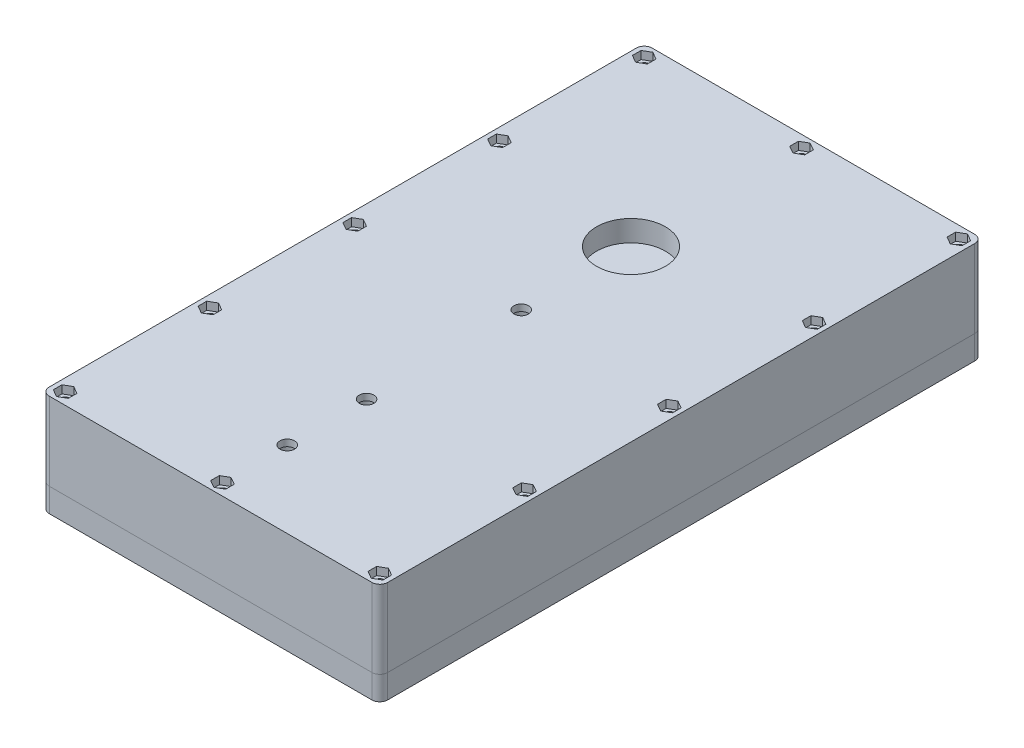
SolidWorks part; units mm, degrees
other "Gearbox lid"
other "Gearbox body"
ref_plane "Front Plane" through (0, 0, 0) normal (0, 0, 1) x (1, 0, 0)
ref_plane "Top Plane" through (0, 0, 0) normal (0, 1, 0) x (1, 0, 0)
ref_plane "Right Plane" through (0, 0, 0) normal (1, 0, 0) x (0, 0, -1)
sketch "Sketch1" plane through (0, 0, 0) normal (0, 1, 0) x (1, 0, 0)
  line L1 (75, -90) -> (-75, -90) construction
  line L2 (75, -90) -> (75, 90) construction
  line L3 (75, 90) -> (-75, 90) construction
  line L4 (-75, -90) -> (-75, 90) construction
  line L5 (0, 90) -> (0, -90) construction
  line L6 (75, 0) -> (-75, 0) construction
  line L7 (15.5, -75.5) -> (-15.5, -75.5) construction
  line L8 (15.5, -75.5) -> (15.5, -44.5) construction
  line L9 (15.5, -44.5) -> (-15.5, -44.5) construction
  line L10 (-15.5, -75.5) -> (-15.5, -44.5) construction
  line L11 (0, -44.5) -> (0, -75.5) construction
  line L12 (15.5, -60) -> (-15.5, -60) construction
  line L13 (-55, 130) -> (55, 130)
  line L14 (-55, 130) -> (-55, -80)
  line L15 (-55, -80) -> (55, -80)
  line L16 (55, 130) -> (55, -80)
  circle A0 centre (0, 70) radius 50 construction
  circle A1 centre (0, 0) radius 20 construction
  circle A3 centre (0, 0) radius 45 construction
  circle A4 centre (0, -60) radius 15 construction
  circle A5 centre (0, 0) radius 3.15
  circle A6 centre (0, -60) radius 2.75
  circle A7 centre (0, 70) radius 13
  point P0 (0, 0)
  dimension "D3" = 160
  dimension "D4" = 31
  dimension "D5" = 30
  dimension "D6" = 90
  dimension "D7" = 40
  dimension "D8" = 130
  dimension "D10" = 26
  dimension "D12" = 6.3
  dimension "D13" = 5.5
  dimension "D14" = 100
  dimension "D2" = 150
  dimension "D9" = 80
  dimension "D11" = 110
extrude "Boss-Extrude1" add sketch "Sketch1" along normal blind 8
sketch "Sketch2" plane through (0, 0, 0) normal (0, -1, 0) x (1, 0, 0)
  line L0 (-64, 89) -> (-64, -139)
  line L1 (-55, 80) -> (55, 80)
  line L2 (-55, 80) -> (-55, -130)
  line L3 (-55, -130) -> (55, -130)
  line L4 (55, 80) -> (55, -130)
  line L5 (-64, -139) -> (64, -139)
  line L6 (64, 89) -> (64, -139)
  line L7 (-64, 89) -> (64, 89)
  line L8 (-55, 80) -> (-64, 89) construction
  line L9 (0, 0) -> (0, 89) construction
  line L10 (-55, -25) -> (55, -25) construction
  line L11 (-64, -25) -> (-55, -25) construction
  line L12 (-59.5, 84.5) -> (-59.5, -25) construction
  line L13 (59.5, 84.5) -> (59.5, -25) construction
  line L14 (64, -25) -> (55, -25) construction
  line L15 (55, 80) -> (64, 89) construction
  line L16 (55, -130) -> (64, -139) construction
  line L17 (0, -50) -> (0, -139) construction
  line L18 (-55, -130) -> (-64, -139) construction
  line L19 (-64, -139) -> (64, -139)
  line L20 (-55, -130) -> (55, -130)
  circle A0 centre (-59.5, 84.5) radius 1.75
  circle A1 centre (-59.5, -25) radius 1.75
  circle A2 centre (-59.5, 29.75) radius 1.75
  circle A3 centre (0, 84.5) radius 1.75
  circle A4 centre (59.5, 29.75) radius 1.75
  circle A5 centre (59.5, -25) radius 1.75
  circle A6 centre (59.5, 84.5) radius 1.75
  circle A7 centre (59.5, -134.5) radius 1.75
  circle A8 centre (59.5, -79.75) radius 1.75
  circle A9 centre (0, -134.5) radius 1.75
  circle A10 centre (-59.5, -79.75) radius 1.75
  circle A11 centre (-59.5, -134.5) radius 1.75
  line M3 (-55, 80) -> (-55, -130)
  line M4 (-55, -130) -> (55, -130)
  line M5 (55, -130) -> (55, 80)
  line M6 (55, 80) -> (-55, 80)
  dimension "D2" = 3.5
  dimension "D1" = 9
extrude "Boss-Extrude2" add sketch "Sketch2" along normal blind 21.5 and the other way up to surface (8 mm away) contours L7 L0 L5 L6 A10 A6 A4 A3 A2 A1 A0 A5 A7 A8 A9 A11 M3 M6 M5 M4 other way up to face at (0, 8, 3.15)
sketch "Sketch3" plane through (0, -21.5, 0) normal (0, -1, 0) x (1, 0, 0)
  line L1 (-64, 89) -> (64, 89)
  line L2 (-64, 89) -> (-64, -139)
  line L3 (-64, -139) -> (64, -139)
  line L4 (64, 89) -> (64, -139)
  line L5 (-15.5, 75.5) -> (15.5, 75.5) construction
  line L6 (-15.5, 75.5) -> (-15.5, 44.5) construction
  line L7 (-15.5, 44.5) -> (15.5, 44.5) construction
  line L8 (15.5, 75.5) -> (15.5, 44.5) construction
  line L9 (0, 44.5) -> (0, 75.5) construction
  line L10 (-15.5, 60) -> (15.5, 60) construction
  circle A0 centre (0, 60) radius 11.5
  circle A1 centre (-15.5, 75.5) radius 1.75
  circle A2 centre (15.5, 75.5) radius 1.75
  circle A3 centre (15.5, 44.5) radius 1.75
  circle A4 centre (-15.5, 44.5) radius 1.75
  circle A5 centre (-59.5, -134.5) radius 1.75 construction
  circle A6 centre (0, -134.5) radius 1.75 construction
  circle A7 centre (59.5, -134.5) radius 1.75 construction
  circle A8 centre (59.5, -79.75) radius 1.75 construction
  circle A9 centre (-59.5, -79.75) radius 1.75 construction
  circle A10 centre (-59.5, -25) radius 1.75 construction
  circle A11 centre (-59.5, 29.75) radius 1.75 construction
  circle A12 centre (59.5, -25) radius 1.75 construction
  circle A13 centre (59.5, 29.75) radius 1.75 construction
  circle A14 centre (59.5, 84.5) radius 1.75 construction
  circle A15 centre (0, 84.5) radius 1.75 construction
  circle A16 centre (-59.5, 84.5) radius 1.75 construction
  circle A17 centre (-59.5, -134.5) radius 1.75
  circle A18 centre (0, -134.5) radius 1.75
  circle A19 centre (59.5, -134.5) radius 1.75
  circle A20 centre (59.5, -79.75) radius 1.75
  circle A21 centre (-59.5, -79.75) radius 1.75
  circle A22 centre (-59.5, -25) radius 1.75
  circle A23 centre (-59.5, 29.75) radius 1.75
  circle A24 centre (59.5, -25) radius 1.75
  circle A25 centre (59.5, 29.75) radius 1.75
  circle A26 centre (59.5, 84.5) radius 1.75
  circle A27 centre (0, 84.5) radius 1.75
  circle A28 centre (-59.5, 84.5) radius 1.75
  circle A29 centre (0, 0) radius 3.15 construction
  circle A30 centre (0, 0) radius 3.15
  circle A31 centre (0, -70) radius 5.25
  point P4 (0, 60)
  dimension "D2" = 23
  dimension "D3" = 3.5
  dimension "D4" = 10.5
  dimension "D1" = 31
extrude "Boss-Extrude3" add sketch "Sketch3" along normal blind 9 separate body
sketch "Sketch4" plane through (0, -21.5, 0) normal (0, 1, 0) x (1, 0, 0)
  circle A0 centre (-15.5, -44.5) radius 2.86
  circle A1 centre (15.5, -44.5) radius 2.86
  circle A2 centre (15.5, -75.5) radius 2.86
  circle A3 centre (-15.5, -75.5) radius 2.86
  dimension "D1" = 5.72
extrude "Cut-Extrude1" cut sketch "Sketch4" against normal blind 3.5
sketch "Sketch5" plane through (0, 0, 0) normal (0, -1, 0) x (1, 0, 0)
  line L0 (0, 0) -> (0, -57) construction
  line L1 (0, 60) -> (0, 0) construction
  circle A0 centre (0, -28.5) radius 2.75
  circle A1 centre (0, 30) radius 2.75
  circle A2 centre (0, -70) radius 13 construction
  dimension "D1" = 5.5
extrude "Cut-Extrude2" cut sketch "Sketch5" against normal through all
sketch "Sketch6" plane through (0, 0, 0) normal (0, -1, 0) x (1, 0, 0)
  circle A0 centre (0, 30) radius 4.36
  circle A1 centre (0, -28.5) radius 4.36
  circle A2 centre (0, 60) radius 4.36
  dimension "D1" = 8.72
extrude "Cut-Extrude3" cut sketch "Sketch6" against normal blind 5.5
sketch "Sketch7" plane through (0, 8, 0) normal (0, 1, 0) x (1, 0, 0)
  circle A0 centre (0, 28.5) radius 7.5
  circle A1 centre (0, -30) radius 7.5
  circle A2 centre (0, -30) radius 2.75 construction
  circle A3 centre (0, 28.5) radius 2.75 construction
  circle A4 centre (0, -30) radius 2.75
  circle A5 centre (0, 28.5) radius 2.75
  dimension "D1" = 15
extrude "Boss-Extrude4" add sketch "Sketch7" along normal blind 22.5 separate body
fillet "Fillet1" radius 3 8 edges at (-55, -10.75, 80) (55, -10.75, 80) (55, -10.75, -130) (-55, -10.75, -130) (-64, -6.75, -139) (64, -6.75, -139) (64, -6.75, 89) (-64, -6.75, 89)
fillet "Fillet2" radius 3 4 edges at (-64, -26, 89) (64, -26, 89) (-64, -26, -139) (64, -26, -139)
sketch "Sketch8" plane through (0, -30.5, 0) normal (0, -1, 0) x (1, 0, 0)
  circle A0 centre (0, 0) radius 3.15 construction
  circle A1 centre (0, 0) radius 3.15
extrude "Boss-Extrude5" add sketch "Sketch8" against normal blind 3
sketch "Sketch9" plane through (0, 8, 0) normal (0, 1, 0) x (1, 0, 0)
  circle A0 centre (0, 0) radius 3.15 construction
  circle A1 centre (0, 0) radius 3.15
extrude "Boss-Extrude6" add sketch "Sketch9" against normal blind 3
sketch "Sketch10" plane through (0, 8, 0) normal (0, 1, 0) x (1, 0, 0)
  line L0 (-59.5, 134.5) -> (-59.5, 137.762) construction
  line L1 (-59.5, 137.762) -> (-62.325, 136.131)
  line L2 (-62.325, 136.131) -> (-62.325, 132.869)
  line L3 (-62.325, 132.869) -> (-59.5, 131.238)
  line L4 (-59.5, 131.238) -> (-56.675, 132.869)
  line L5 (-56.675, 132.869) -> (-56.675, 136.131)
  line L6 (-56.675, 136.131) -> (-59.5, 137.762)
  line L7 (0, 137.762) -> (-2.825, 136.131)
  line L8 (-2.825, 136.131) -> (-2.825, 132.869)
  line L9 (-2.825, 132.869) -> (0, 131.238)
  line L10 (0, 131.238) -> (2.825, 132.869)
  line L11 (2.825, 132.869) -> (2.825, 136.131)
  line L12 (2.825, 136.131) -> (0, 137.762)
  line L13 (-59.5, 83.012) -> (-62.325, 81.381)
  line L14 (-62.325, 81.381) -> (-62.325, 78.119)
  line L15 (-62.325, 78.119) -> (-59.5, 76.488)
  line L16 (-59.5, 76.488) -> (-56.675, 78.119)
  line L17 (-56.675, 78.119) -> (-56.675, 81.381)
  line L18 (-56.675, 81.381) -> (-59.5, 83.012)
  line L19 (-59.5, 28.262) -> (-62.325, 26.631)
  line L20 (-62.325, 26.631) -> (-62.325, 23.369)
  line L21 (-62.325, 23.369) -> (-59.5, 21.738)
  line L22 (-59.5, 21.738) -> (-56.675, 23.369)
  line L23 (-56.675, 23.369) -> (-56.675, 26.631)
  line L24 (-56.675, 26.631) -> (-59.5, 28.262)
  line L25 (-59.5, 79.75) -> (-59.5, 83.012) construction
  line L26 (-59.5, 25) -> (-59.5, 28.262) construction
  line L27 (0, 134.5) -> (0, 137.762) construction
  line L28 (64, 25) -> (-64, 25) construction
  line L29 (-64, -86) -> (-64, 136) construction
  line L30 (64, -86) -> (64, 136) construction
  line L31 (0, 25) -> (0, 0) construction
  line L32 (59.5, 25) -> (59.5, 28.262) construction
  line L33 (59.5, 79.75) -> (59.5, 83.012) construction
  line L34 (59.5, 134.5) -> (59.5, 137.762) construction
  line L35 (56.675, 26.631) -> (59.5, 28.262)
  line L36 (56.675, 23.369) -> (56.675, 26.631)
  line L37 (59.5, 21.738) -> (56.675, 23.369)
  line L38 (62.325, 23.369) -> (59.5, 21.738)
  line L39 (62.325, 26.631) -> (62.325, 23.369)
  line L40 (59.5, 28.262) -> (62.325, 26.631)
  line L41 (56.675, 81.381) -> (59.5, 83.012)
  line L42 (56.675, 78.119) -> (56.675, 81.381)
  line L43 (59.5, 76.488) -> (56.675, 78.119)
  line L44 (62.325, 78.119) -> (59.5, 76.488)
  line L45 (62.325, 81.381) -> (62.325, 78.119)
  line L46 (59.5, 83.012) -> (62.325, 81.381)
  line L47 (56.675, 136.131) -> (59.5, 137.762)
  line L48 (56.675, 132.869) -> (56.675, 136.131)
  line L49 (59.5, 131.238) -> (56.675, 132.869)
  line L50 (62.325, 132.869) -> (59.5, 131.238)
  line L51 (62.325, 136.131) -> (62.325, 132.869)
  line L52 (59.5, 137.762) -> (62.325, 136.131)
  line L53 (59.5, -84.5) -> (59.5, -87.762) construction
  line L54 (59.5, -29.75) -> (59.5, -33.012) construction
  line L55 (0, -84.5) -> (0, -87.762) construction
  line L56 (-59.5, -29.75) -> (-59.5, -33.012) construction
  line L57 (-59.5, -84.5) -> (-59.5, -87.762) construction
  line L58 (59.5, -87.762) -> (62.325, -86.131)
  line L59 (62.325, -86.131) -> (62.325, -82.869)
  line L60 (62.325, -82.869) -> (59.5, -81.238)
  line L61 (59.5, -81.238) -> (56.675, -82.869)
  line L62 (56.675, -82.869) -> (56.675, -86.131)
  line L63 (56.675, -86.131) -> (59.5, -87.762)
  line L64 (59.5, -33.012) -> (62.325, -31.381)
  line L65 (62.325, -31.381) -> (62.325, -28.119)
  line L66 (62.325, -28.119) -> (59.5, -26.488)
  line L67 (59.5, -26.488) -> (56.675, -28.119)
  line L68 (56.675, -28.119) -> (56.675, -31.381)
  line L69 (56.675, -31.381) -> (59.5, -33.012)
  line L70 (-56.675, -31.381) -> (-59.5, -33.012)
  line L71 (-56.675, -28.119) -> (-56.675, -31.381)
  line L72 (-59.5, -26.488) -> (-56.675, -28.119)
  line L73 (-62.325, -28.119) -> (-59.5, -26.488)
  line L74 (-62.325, -31.381) -> (-62.325, -28.119)
  line L75 (-59.5, -33.012) -> (-62.325, -31.381)
  line L76 (2.825, -86.131) -> (0, -87.762)
  line L77 (2.825, -82.869) -> (2.825, -86.131)
  line L78 (0, -81.238) -> (2.825, -82.869)
  line L79 (-2.825, -82.869) -> (0, -81.238)
  line L80 (-2.825, -86.131) -> (-2.825, -82.869)
  line L81 (0, -87.762) -> (-2.825, -86.131)
  line L82 (-56.675, -86.131) -> (-59.5, -87.762)
  line L83 (-56.675, -82.869) -> (-56.675, -86.131)
  line L84 (-59.5, -81.238) -> (-56.675, -82.869)
  line L85 (-62.325, -82.869) -> (-59.5, -81.238)
  line L86 (-62.325, -86.131) -> (-62.325, -82.869)
  line L87 (-59.5, -87.762) -> (-62.325, -86.131)
  circle A0 centre (-59.5, 134.5) radius 2.825 construction
  circle A1 centre (0, 134.5) radius 2.825 construction
  circle A2 centre (-59.5, 79.75) radius 2.825 construction
  circle A3 centre (-59.5, 25) radius 2.825 construction
  circle A4 centre (59.5, 25) radius 2.825 construction
  circle A5 centre (59.5, 79.75) radius 2.825 construction
  circle A6 centre (59.5, 134.5) radius 2.825 construction
  circle A7 centre (59.5, -84.5) radius 2.825 construction
  circle A8 centre (59.5, -29.75) radius 2.825 construction
  circle A9 centre (-59.5, -29.75) radius 2.825 construction
  circle A10 centre (0, -84.5) radius 2.825 construction
  circle A11 centre (-59.5, -84.5) radius 2.825 construction
  dimension "D1" = 5.65
extrude "Cut-Extrude4" cut sketch "Sketch10" against normal blind 3
chamfer "Chamfer1" distance 2 angle 45 1 edges at (0, -21.5, 48.5)
chamfer "Chamfer2" distance 1 angle 45 4 edges at (0, 0, 3.15) (0, 0, 55.64) (0, 0, 25.64) (0, 0, -32.86)
chamfer "Chamfer3" distance 1 angle 45 2 edges at (0, -21.5, -3.15) (0, -21.5, -75.25)
delete or keep bodies "Body-Delete/Keep 1" type delete bodies bodies 107
delete or keep bodies "Body-Delete/Keep 2" type delete bodies bodies 108
other "Save Bodies1"
